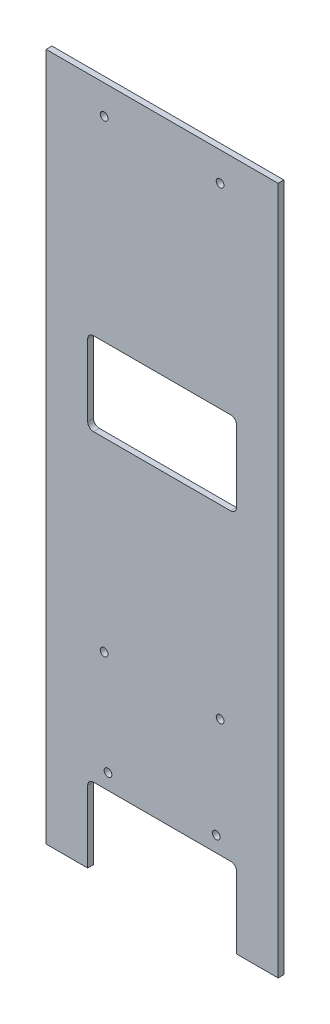
SolidWorks part; units mm, degrees
ref_plane "Front Plane" through (0, 0, 0) normal (0, 0, 1) x (1, 0, 0)
ref_plane "Top Plane" through (0, 0, 0) normal (0, 1, 0) x (1, 0, 0)
ref_plane "Right Plane" through (0, 0, 0) normal (1, 0, 0) x (0, 0, -1)
sketch "Sketch1" plane through (0, 0, 0) normal (0, 0, 1) x (1, 0, 0)
  line L1 (60, -200) -> (-60, -200)
  line L2 (60, -200) -> (60, 200)
  line L3 (60, 200) -> (-60, 200)
  line L4 (-60, -200) -> (-60, 200)
  line L5 (60, -200) -> (-60, 200) construction
  line L6 (60, 200) -> (-60, -200) construction
  point P0 (0, 0)
  dimension "D1" = 120
  dimension "D2" = 400
extrude "Boss-Extrude1" add sketch "Sketch1" along normal blind 3
sketch "Sketch2" plane through (0, 0, 3) normal (0, 0, 1) x (1, 0, 0)
  line L0 (-34.5, -117) -> (34.5, -117) construction
  line L1 (-35.5, -116) -> (35.5, -116)
  line L2 (-38.5, -119) -> (-38.5, -156)
  line L3 (-35.5, -159) -> (35.5, -159)
  line L4 (38.5, -119) -> (38.5, -156)
  line L5 (37.5, -123) -> (37.5, -120) construction
  line L6 (-75, -158) -> (75, -158) construction
  line L7 (-37.5, -146) -> (-37.5, -124) construction
  line L8 (-35.5, 84) -> (35.5, 84)
  line L9 (-38.5, 81) -> (-38.5, 44)
  line L10 (-35.5, 41) -> (35.5, 41)
  line L11 (38.5, 81) -> (38.5, 44)
  arc A0 (35.5, -159) -> (38.5, -156) centre (35.5, -156) ccw
  arc A1 (-35.5, -159) -> (-38.5, -156) centre (-35.5, -156) cw
  arc A2 (38.5, -119) -> (35.5, -116) centre (35.5, -119) ccw
  arc A3 (-35.5, -116) -> (-38.5, -119) centre (-35.5, -119) ccw
  arc A4 (35.5, 41) -> (38.5, 44) centre (35.5, 44) ccw
  arc A5 (-35.5, 41) -> (-38.5, 44) centre (-35.5, 44) cw
  arc A6 (38.5, 81) -> (35.5, 84) centre (35.5, 81) ccw
  arc A7 (-35.5, 84) -> (-38.5, 81) centre (-35.5, 81) ccw
  dimension "D5" = 3
  dimension "D1" = 1
  dimension "D2" = 1
  dimension "D3" = 1
  dimension "D4" = 1
extrude "Cut-Extrude1" cut sketch "Sketch2" against normal blind 3
sketch "Sketch3" plane through (0, 0, 3) normal (0, 0, 1) x (1, 0, 0)
  line L0 (-60, 200) -> (-60, -200) construction
  line L1 (60, 200) -> (-60, 200) construction
  line L2 (0, -1.65) -> (0, 1.65) construction
  circle A0 centre (-30, 185) radius 2
  circle A1 centre (-30, 65) radius 2
  circle A2 centre (-30, -55) radius 2
  circle A3 centre (-30, -175) radius 2
  circle A4 centre (30, -175) radius 2
  circle A5 centre (30, -55) radius 2
  circle A6 centre (30, 65) radius 2
  circle A7 centre (30, 185) radius 2
  dimension "D1" = 30
  dimension "D2" = 15
extrude "Cut-Extrude2" cut sketch "Sketch3" against normal blind 3
sketch "Sketch4" plane through (0, 0, 3) normal (0, 0, 1) x (1, 0, 0)
  line L0 (60, -200) -> (60, 200) construction
  line L1 (-60, -200) -> (60, -200)
  line L2 (-60, -200) -> (-60, -156)
  line L3 (-60, -156) -> (60, -156)
  line L4 (60, -200) -> (60, -156)
  dimension "D1" = 0
extrude "Cut-Extrude3" cut sketch "Sketch4" against normal blind 10
sketch "Sketch5" plane through (0, 0, 3) normal (0, 0, 1) x (1, 0, 0)
  line L0 (35.5, -116) -> (-35.5, -116) construction
  line L1 (0, -1.65) -> (0, 1.65) construction
  circle A0 centre (-28, -108) radius 2
  circle A1 centre (28, -108) radius 2
  dimension "D1" = 8
extrude "Cut-Extrude4" cut sketch "Sketch5" against normal blind 10
